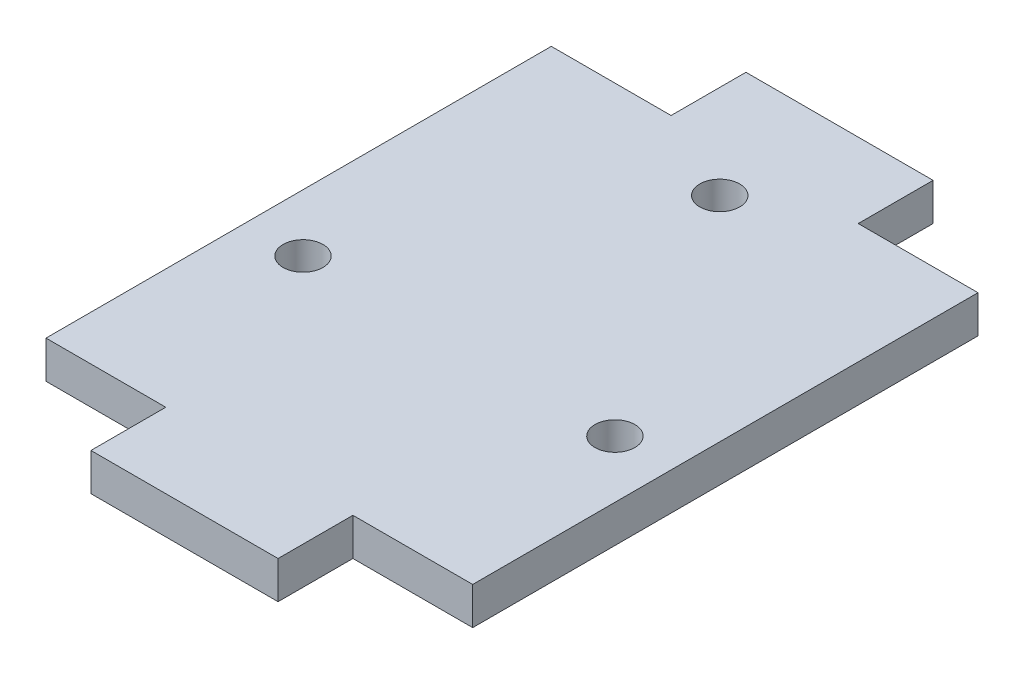
SolidWorks part; units mm, degrees
ref_plane "Plano frontal" through (0, 0, 0) normal (0, 0, 1) x (1, 0, 0)
ref_plane "Plano superior" through (0, 0, 0) normal (0, 1, 0) x (1, 0, 0)
ref_plane "Plano direito" through (0, 0, 0) normal (1, 0, 0) x (0, 0, -1)
ref_plane "Plano1" through (0, -6, 0) normal (0, -1, 0) x (1, 0, 0)
sketch "Esboço1" plane through (0, -6, 0) normal (0, -1, 0) x (1, 0, 0)
  line L0 (17.1, 36.9) -> (7.5, 36.9)
  line L1 (7.5, 36.9) -> (7.5, 42.9)
  line L2 (7.5, 42.9) -> (-7.5, 42.9)
  line L3 (-7.5, 42.9) -> (-7.5, 36.9)
  line L4 (-7.5, 36.9) -> (-17.1, 36.9)
  line L5 (-17.1, 36.9) -> (-17.1, -3.6)
  line L6 (-17.1, -3.6) -> (-7.5, -3.6)
  line L7 (-7.5, -3.6) -> (-7.5, -9.6)
  line L8 (-7.5, -9.6) -> (7.5, -9.6)
  line L9 (7.5, -9.6) -> (7.5, -3.6)
  line L10 (7.5, -3.6) -> (17.1, -3.6)
  line L11 (17.1, -3.6) -> (17.1, 36.9)
  line L12 (-12.5, 20.9) -> (12.5, 20.9) construction
  line L13 (-7.5, 36.9) -> (7.5, 36.9) construction
  circle A0 centre (-12.5, 20.9) radius 1.6
  circle A1 centre (0, 0) radius 1.6
  circle A2 centre (12.5, 20.9) radius 1.6
  point P18 (0, 20.9)
  point P19 (0, 36.9)
  dimension "D5" = 3.2
  dimension "D1" = 25
  dimension "D2" = 40.5
  dimension "D3" = 6
  dimension "D4" = 15
  dimension "D6" = 20.9
  dimension "D7" = 34.2
  dimension "D8" = 3.6
extrude "Ressalto-extrusão1" add sketch "Esboço1" against normal blind 3
